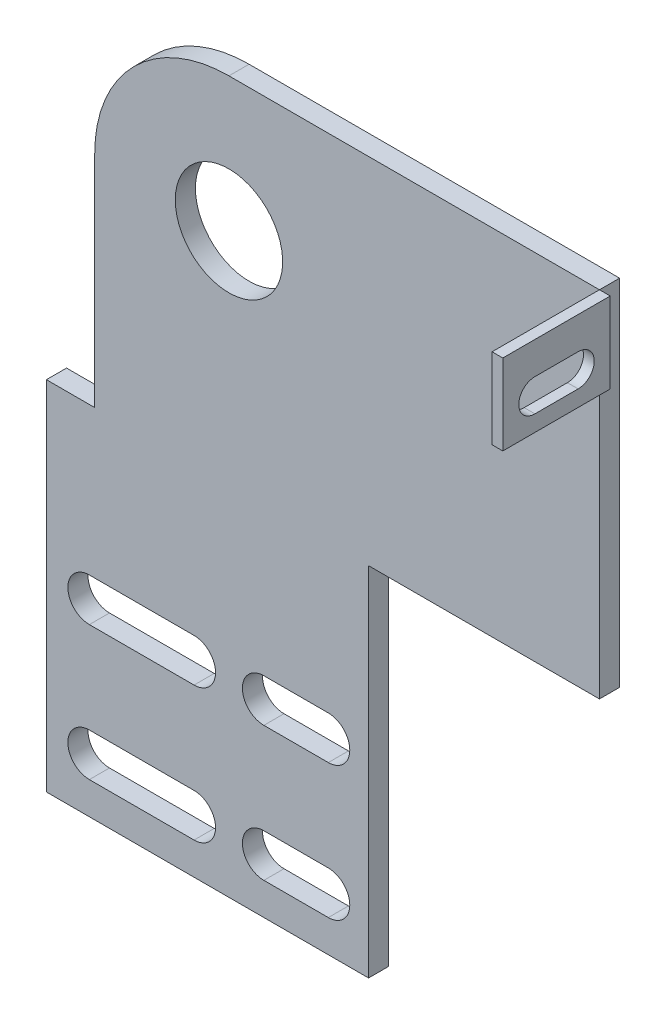
SolidWorks part; units mm, degrees
ref_plane "Front Plane" through (0, 0, 0) normal (0, 0, 1) x (1, 0, 0)
ref_plane "Top Plane" through (0, 0, 0) normal (0, 1, 0) x (1, 0, 0)
ref_plane "Right Plane" through (0, 0, 0) normal (1, 0, 0) x (0, 0, -1)
sketch "Sketch1" plane through (0, 0, 0) normal (0, 0, 1) x (1, 0, 0)
  line L1 (0, 0) -> (130.81, 0)
  line L2 (0, 0) -> (0, 168.275)
  line L3 (0, 168.275) -> (130.81, 168.275)
  line L4 (130.81, 0) -> (130.81, 168.275)
  dimension "D1" = 130.81
  dimension "D2" = 168.275
extrude "Boss-Extrude1" add sketch "Sketch1" along normal blind 4.7625
sketch "Sketch2" plane through (0, 0, 0) normal (0, 0, 1) x (1, 0, 0)
  line L0 (0, 84.455) -> (11.43, 84.455)
  line L1 (0, 168.275) -> (0, 0) construction
  line L2 (11.43, 84.455) -> (11.43, 136.525)
  line L3 (130.81, 168.275) -> (0, 168.275) construction
  line L4 (43.18, 168.275) -> (130.81, 168.275)
  line L5 (130.81, 168.275) -> (130.81, 84.455)
  line L6 (130.81, 0) -> (130.81, 168.275) construction
  line L7 (130.81, 84.455) -> (76.2, 84.455)
  line L8 (76.2, 84.455) -> (76.2, 0)
  line L9 (0, 0) -> (130.81, 0) construction
  line L10 (76.2, 0) -> (0, 0)
  line L11 (0, 0) -> (0, 84.455)
  line L12 (10.16, 44.45) -> (34.925, 44.45) construction
  line L13 (10.16, 49.53) -> (34.925, 49.53)
  line L14 (10.16, 39.37) -> (34.925, 39.37)
  line L15 (10.16, 12.7) -> (34.925, 12.7) construction
  line L16 (10.16, 17.78) -> (34.925, 17.78)
  line L17 (10.16, 7.62) -> (34.925, 7.62)
  line L18 (51.435, 44.45) -> (66.675, 44.45) construction
  line L19 (51.435, 49.53) -> (66.675, 49.53)
  line L20 (51.435, 39.37) -> (66.675, 39.37)
  line L21 (51.435, 12.7) -> (66.675, 12.7) construction
  line L22 (51.435, 17.78) -> (66.675, 17.78)
  line L23 (51.435, 7.62) -> (66.675, 7.62)
  arc A0 (11.43, 136.525) -> (43.18, 168.275) centre (43.18, 136.525) cw
  circle A1 centre (43.18, 136.525) radius 12.7
  arc A2 (10.16, 49.53) -> (10.16, 39.37) centre (10.16, 44.45) ccw
  arc A3 (34.925, 39.37) -> (34.925, 49.53) centre (34.925, 44.45) ccw
  arc A4 (10.16, 17.78) -> (10.16, 7.62) centre (10.16, 12.7) ccw
  arc A5 (34.925, 7.62) -> (34.925, 17.78) centre (34.925, 12.7) ccw
  arc A6 (51.435, 49.53) -> (51.435, 39.37) centre (51.435, 44.45) ccw
  arc A7 (66.675, 39.37) -> (66.675, 49.53) centre (66.675, 44.45) ccw
  arc A8 (51.435, 17.78) -> (51.435, 7.62) centre (51.435, 12.7) ccw
  arc A9 (66.675, 7.62) -> (66.675, 17.78) centre (66.675, 12.7) ccw
  point P23 (22.5425, 44.45)
  point P30 (22.5425, 12.7)
  point P37 (59.055, 44.45)
  point P44 (59.055, 12.7)
  point P49 (5.08, 44.45)
  point P50 (40.005, 44.45)
  point P51 (46.355, 44.45)
  point P52 (71.755, 44.45)
  dimension "D4" = 25.4
  dimension "D5" = 119.38
  dimension "D6" = 10.16
  dimension "D12" = 10.16
  dimension "D14" = 31.75
  dimension "D2" = 76.2
  dimension "D3" = 83.82
  dimension "D7" = 34.925
  dimension "D8" = 25.4
  dimension "D9" = 5.08
  dimension "D10" = 12.7
  dimension "D11" = 44.45
  dimension "D13" = 6.35
extrude "Cut-Extrude1" cut sketch "Sketch2" along normal through all flip side to cut
ref_plane "Plane1" through (130.81, 0, 0) normal (1, 0, 0) x (0, 0, -1)
sketch "Sketch3" plane through (130.81, 0, 0) normal (1, 0, 0) x (0, 0, -1)
  line L0 (-22.5728, 156.845) -> (-12.3522, 156.845) construction
  line L1 (-4.7625, 168.275) -> (-30.1625, 168.275)
  line L2 (-4.7625, 168.275) -> (-4.7625, 149.225)
  line L3 (-4.7625, 149.225) -> (-30.1625, 149.225)
  line L4 (-30.1625, 168.275) -> (-30.1625, 149.225)
  line L5 (-22.5728, 160.655) -> (-12.3522, 160.655)
  line L6 (-22.5728, 153.035) -> (-12.3522, 153.035)
  arc A0 (-22.5728, 160.655) -> (-22.5728, 153.035) centre (-22.5728, 156.845) ccw
  arc A1 (-12.3522, 153.035) -> (-12.3522, 160.655) centre (-12.3522, 156.845) ccw
  point P7 (-17.4625, 156.845)
  point P12 (-17.4625, 168.275)
  dimension "D3" = 3.81
  dimension "D1" = 25.4
  dimension "D2" = 19.05
  dimension "D4" = 7.62
extrude "Boss-Extrude2" add sketch "Sketch3" along normal blind 2.54 separate body
